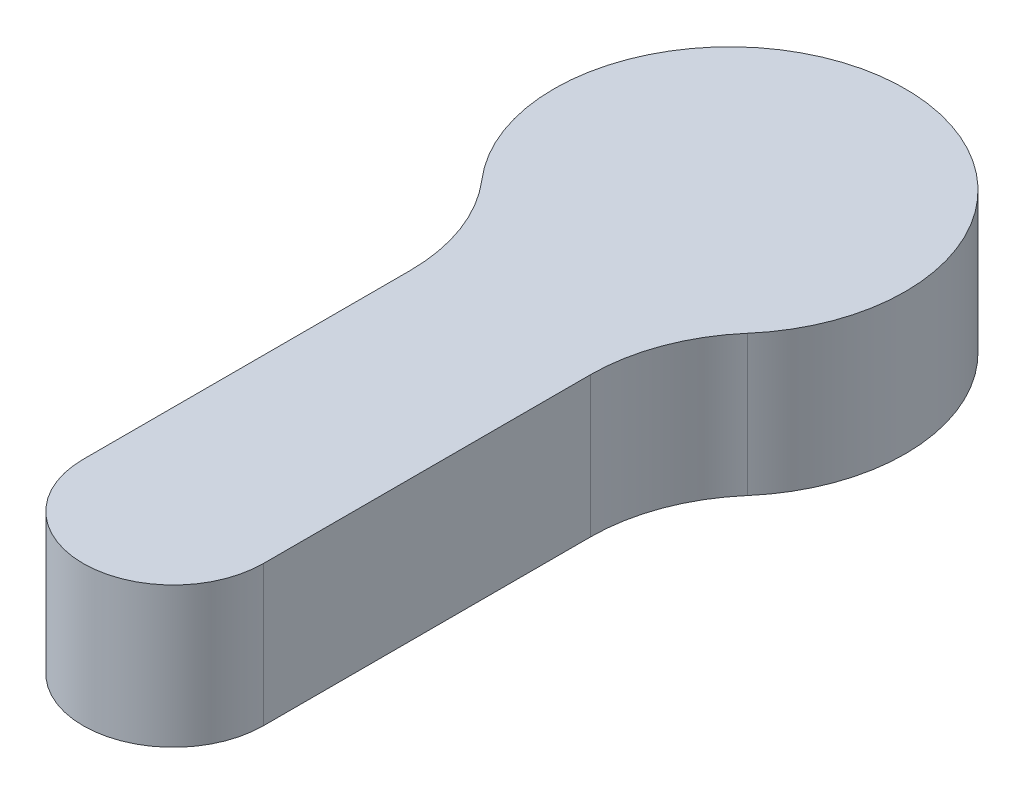
SolidWorks part; units mm, degrees
ref_plane "Front Plane" through (0, 0, 0) normal (0, 0, 1) x (1, 0, 0)
ref_plane "Top Plane" through (0, 0, 0) normal (0, 1, 0) x (1, 0, 0)
ref_plane "Right Plane" through (0, 0, 0) normal (1, 0, 0) x (0, 0, -1)
sketch "Sketch2" plane through (0, 0, 0) normal (0, 1, 0) x (1, 0, 0)
  line L2 (-3.7973, -13.7656) -> (-3.7973, 0)
  line L4 (3.7973, -13.7656) -> (3.7973, 0)
  arc A1 (5.5933, 4.8201) -> (-5.5933, 4.8201) centre (0, 9.6604) ccw
  arc A2 (-3.7973, -13.7656) -> (3.7973, -13.7656) centre (0, -13.7656) ccw
  arc A3 (3.7973, 0) -> (5.5933, 4.8201) centre (11.1633, 0) cw
  arc A4 (-3.7973, 0) -> (-5.5933, 4.8201) centre (-11.1633, 0) ccw
  point P0 (0, 0)
  point P4 (0, -17.5629)
  point P10 (0, 17.0573)
  dimension "D2" = 34.6202
  dimension "D3" = 7.366
  dimension "D1" = 7.5946
extrude "Boss-Extrude1" add sketch "Sketch2" along normal blind 5.9182
